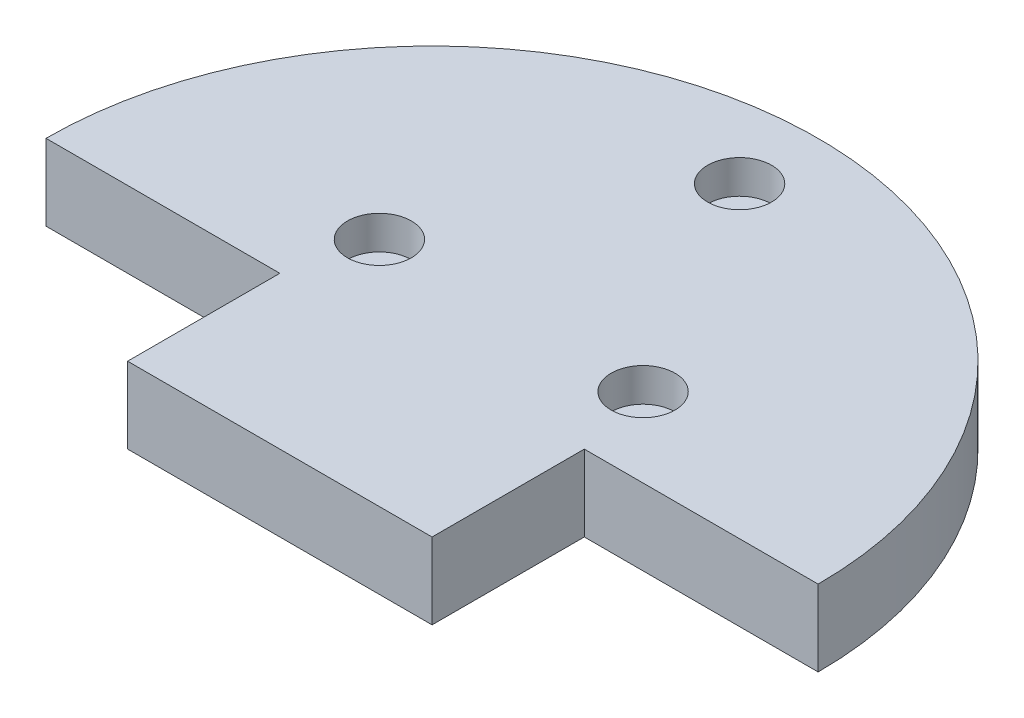
SolidWorks part; units mm, degrees
ref_plane "Alzado" through (0, 0, 0) normal (0, 0, 1) x (1, 0, 0)
ref_plane "Planta" through (0, 0, 0) normal (0, 1, 0) x (1, 0, 0)
ref_plane "Vista lateral" through (0, 0, 0) normal (1, 0, 0) x (0, 0, -1)
sketch "Croquis1" plane through (0, 0, 0) normal (0, 1, 0) x (1, 0, 0)
  line L0 (-10, 0) -> (10, 0)
  line L1 (-10, 0) -> (-10, 10)
  line L2 (-10, 10) -> (-25.36, 10)
  line L3 (10, 0) -> (10, 10)
  line L4 (10, 10) -> (25.36, 10)
  arc A0 (-25.36, 10) -> (25.36, 10) centre (0, 10) cw
  dimension "D4" = 25.36
  dimension "D1" = 20
  dimension "D2" = 10
  dimension "D3" = 15.36
extrude "Saliente-Extruir1" add sketch "Croquis1" along normal blind 5
sketch "Croquis2" plane through (0, 5, 0) normal (0, 1, 0) x (1, 0, 0)
  line L0 (0, 30.2) -> (0, 15.2) construction
  line L1 (-8.66, 15.2) -> (8.66, 15.2) construction
  line L2 (0, 30.2) -> (-8.66, 15.2) construction
  line L3 (0, 30.2) -> (8.66, 15.2) construction
  line L4 (-10, 0) -> (10, 0) construction
  circle A0 centre (0, 30.2) radius 2.1
  circle A1 centre (8.66, 15.2) radius 2.1
  circle A2 centre (-8.66, 15.2) radius 2.1
  point P3 (0, 22.7)
  dimension "D4" = 4.2
  dimension "D1" = 15
  dimension "D2" = 17.32
  dimension "D3" = 22.7
extrude "Cortar-Extruir1" cut sketch "Croquis2" against normal blind 2.2
sketch "Croquis3" plane through (0, 5, 0) normal (0, 1, 0) x (1, 0, 0)
  circle A0 centre (-8.66, 15.2) radius 1
  circle A1 centre (8.66, 15.2) radius 1
  circle A2 centre (0, 30.2) radius 1
  dimension "D1" = 2
extrude "Cortar-Extruir2" cut sketch "Croquis3" against normal blind 10
